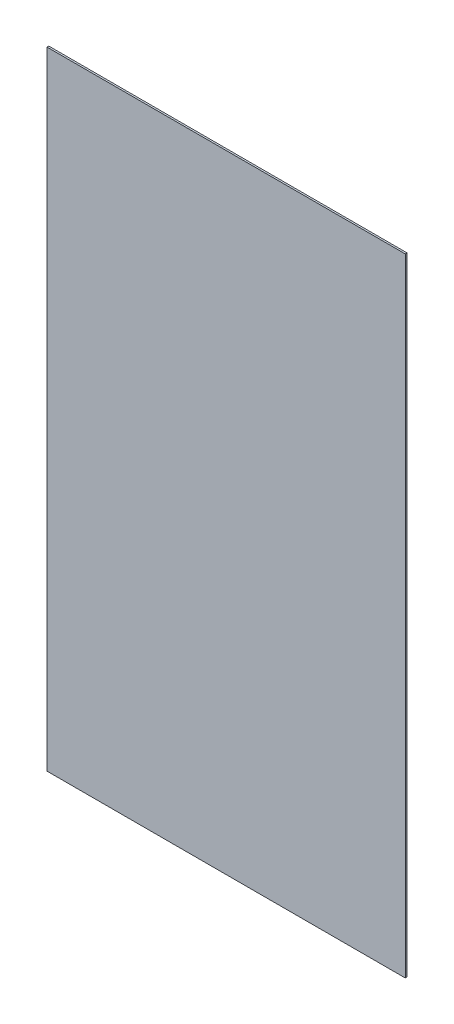
SolidWorks part; units mm, degrees
ref_plane "Front Plane" through (0, 0, 0) normal (0, 0, 1) x (1, 0, 0)
ref_plane "Top Plane" through (0, 0, 0) normal (0, 1, 0) x (1, 0, 0)
ref_plane "Right Plane" through (0, 0, 0) normal (1, 0, 0) x (0, 0, -1)
sketch "Sketch1" plane through (0, 0, 0) normal (0, 0, 1) x (1, 0, 0)
  line L1 (-254, -444.5) -> (254, -444.5)
  line L2 (-254, -444.5) -> (-254, 444.5)
  line L3 (-254, 444.5) -> (254, 444.5)
  line L4 (254, -444.5) -> (254, 444.5)
  line L5 (-254, -444.5) -> (254, 444.5) construction
  line L6 (-254, 444.5) -> (254, -444.5) construction
  point P0 (0, 0)
  dimension "D1" = 889
  dimension "D2" = 508
extrude "Boss-Extrude1" add sketch "Sketch1" along normal blind 2.54
